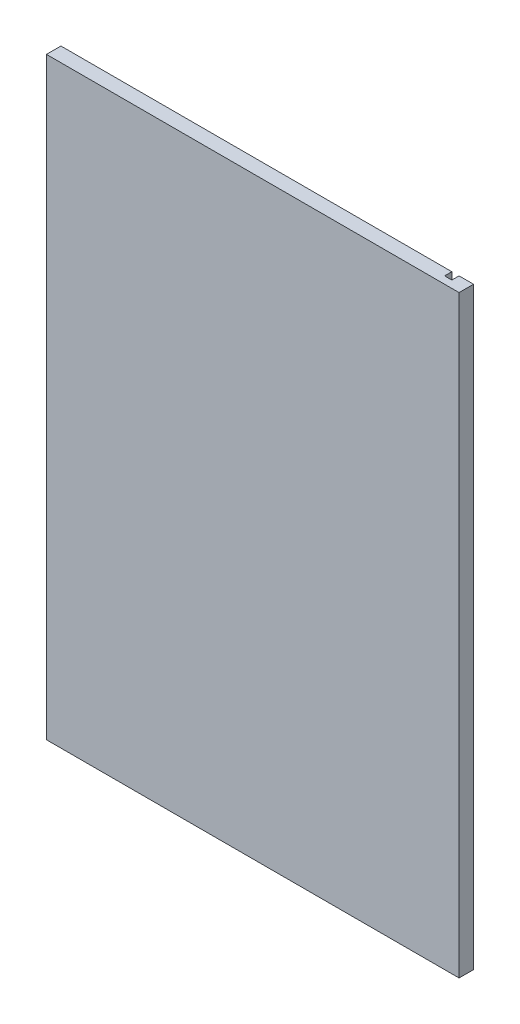
SolidWorks part; units mm, degrees
ref_plane "Plan de face" through (0, 0, 0) normal (0, 0, 1) x (1, 0, 0)
ref_plane "Plan de dessus" through (0, 0, 0) normal (0, 1, 0) x (1, 0, 0)
ref_plane "Plan de droite" through (0, 0, 0) normal (1, 0, 0) x (0, 0, -1)
sketch "Esquisse1" plane through (0, 0, 0) normal (0, 0, 1) x (1, 0, 0)
  line L1 (0, 0) -> (-285, 0)
  line L2 (0, 0) -> (0, 410)
  line L3 (0, 410) -> (-285, 410)
  line L4 (-285, 0) -> (-285, 410)
  dimension "D1" = 285
  dimension "D2" = 410
extrude "Boss.-Extru.1" add sketch "Esquisse1" along normal blind 10
sketch "Esquisse2" plane through (0, 0, 0) normal (0, 0, -1) x (-1, 0, 0)
  line L0 (0, 410) -> (285, 410) construction
  line L1 (10, 410) -> (15, 410)
  line L2 (10, 410) -> (10, 0)
  line L3 (10, 0) -> (15, 0)
  line L4 (15, 410) -> (15, 0)
  line L5 (285, 0) -> (0, 0) construction
  dimension "D1" = 10
  dimension "D2" = 5
extrude "Enlèv. mat.-Extru.1" cut sketch "Esquisse2" against normal blind 5
